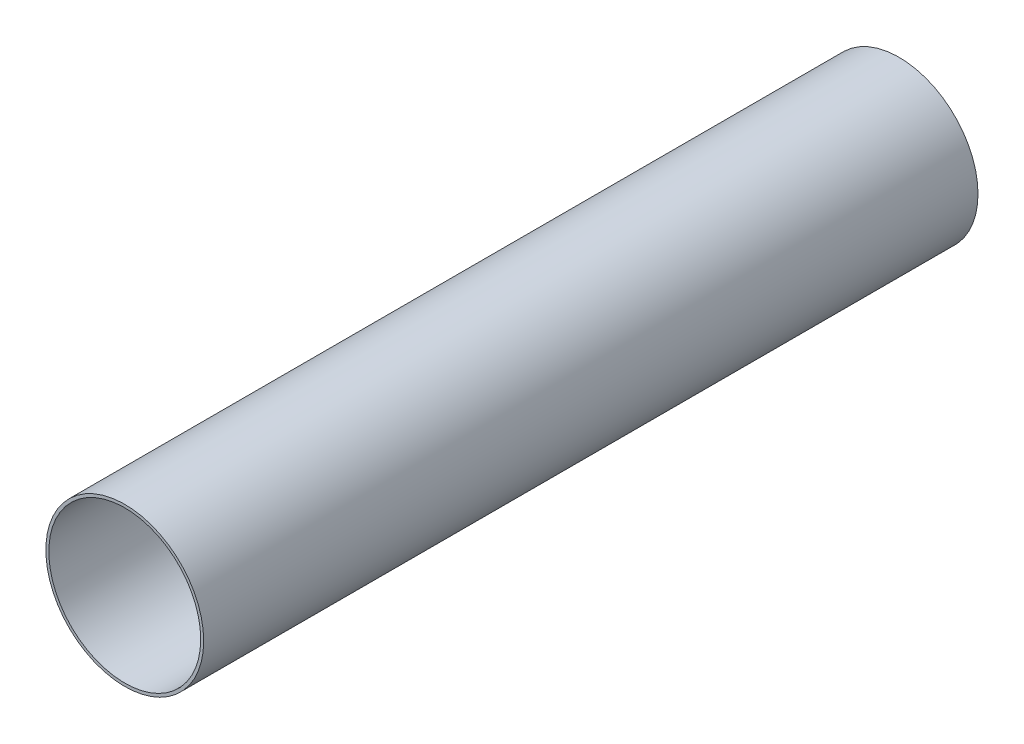
SolidWorks part; units mm, degrees
ref_plane "Front Plane" through (0, 0, 0) normal (0, 0, 1) x (1, 0, 0)
ref_plane "Top Plane" through (0, 0, 0) normal (0, 1, 0) x (1, 0, 0)
ref_plane "Right Plane" through (0, 0, 0) normal (1, 0, 0) x (0, 0, -1)
sketch "Sketch1" plane through (0, 0, 0) normal (0, 0, 1) x (1, 0, 0)
  circle A0 centre (0, 0) radius 13.25
  dimension "D1" = 26.5
extrude "Boss-Extrude1" add sketch "Sketch1" along normal blind 130
sketch "Sketch2" plane through (0, 0, 130) normal (0, 0, 1) x (1, 0, 0)
  circle A0 centre (0, 0) radius 12.75
  dimension "D1" = 25.5
extrude "Cut-Extrude1" cut sketch "Sketch2" against normal through all
